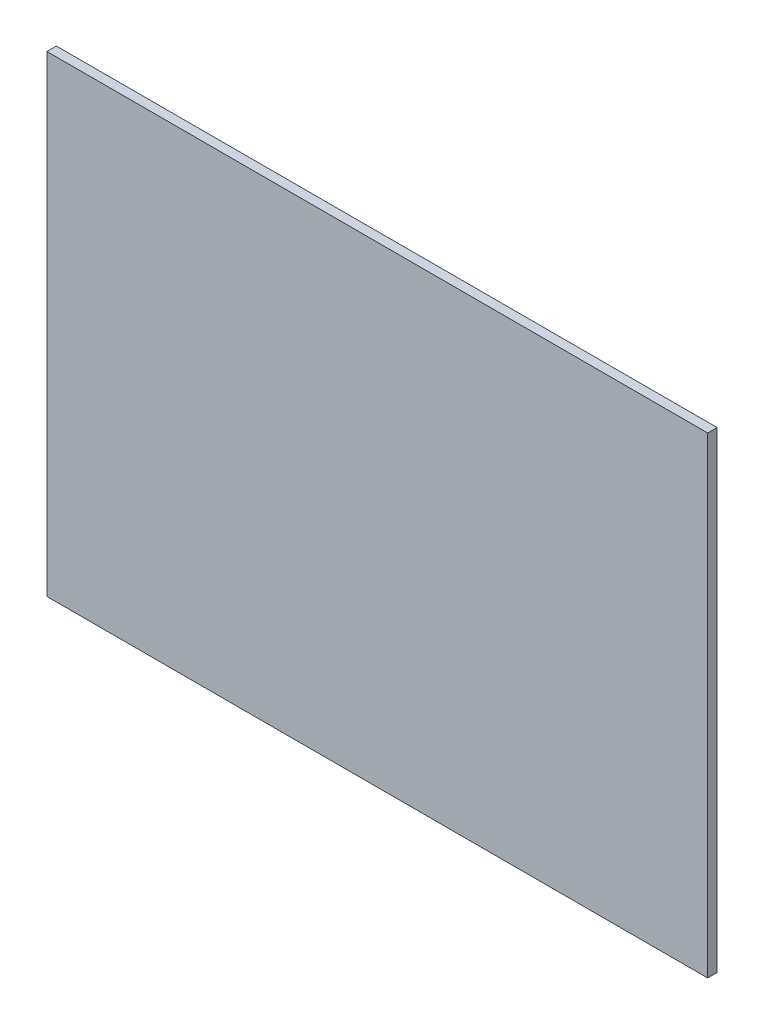
SolidWorks part; units mm, degrees
material "Balsa"
ref_plane "Plan de face" through (0, 0, 0) normal (0, 0, 1) x (1, 0, 0)
ref_plane "Plan de dessus" through (0, 0, 0) normal (0, 1, 0) x (1, 0, 0)
ref_plane "Plan de droite" through (0, 0, 0) normal (1, 0, 0) x (0, 0, -1)
sketch "Esquisse1" plane through (0, 0, 0) normal (0, 0, 1) x (1, 0, 0)
  line L1 (0, 0) -> (-700, 0)
  line L2 (0, 0) -> (0, 500)
  line L3 (0, 500) -> (-700, 500)
  line L4 (-700, 0) -> (-700, 500)
  dimension "D1" = 700
  dimension "D2" = 500
extrude "Boss.-Extru.1" add sketch "Esquisse1" along normal blind 10
